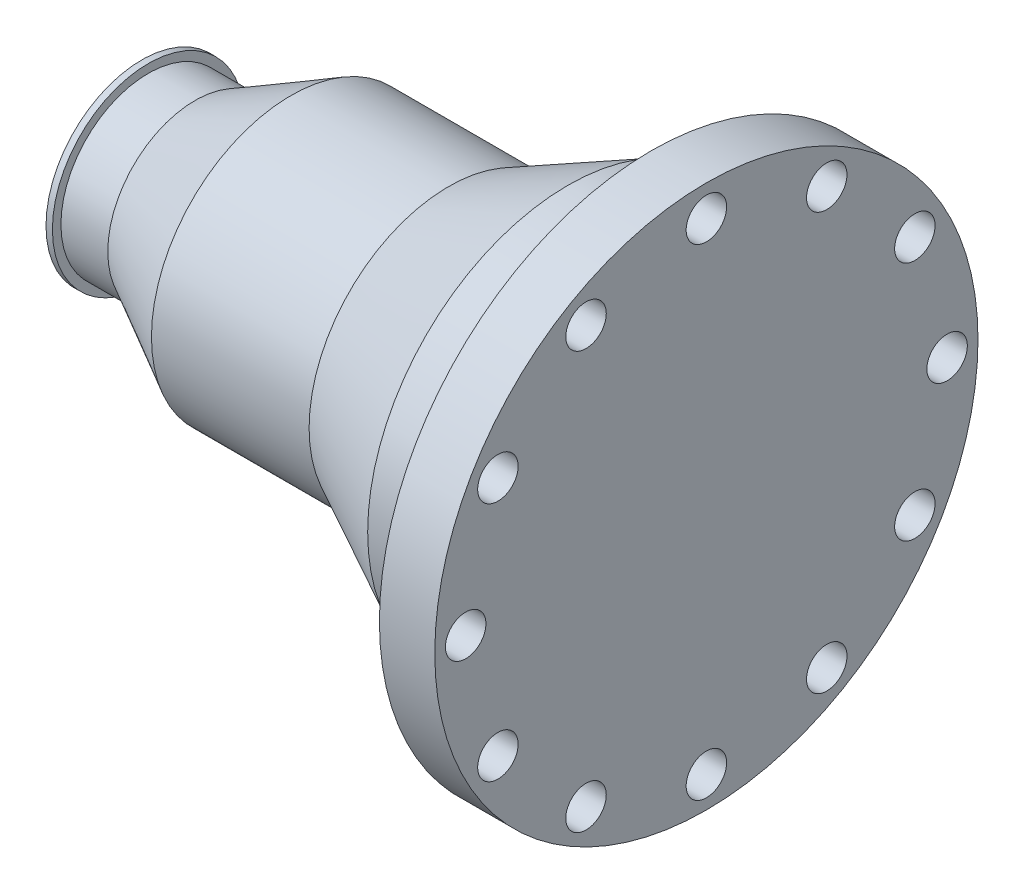
SolidWorks part; units mm, degrees
ref_plane "Спереди" through (0, 0, 0) normal (0, 0, 1) x (1, 0, 0)
ref_plane "Сверху" through (0, 0, 0) normal (0, 1, 0) x (1, 0, 0)
ref_plane "Справа" through (0, 0, 0) normal (1, 0, 0) x (0, 0, -1)
sketch "Эскиз1" plane through (0, 0, 0) normal (0, 0, 1) x (1, 0, 0)
  line L0 (0, 0) -> (265, 0)
  line L1 (0, 0) -> (0, 45)
  line L2 (0, 45) -> (3, 45)
  line L3 (3, 45) -> (3, 41)
  line L4 (3, 41) -> (25, 41)
  line L5 (25, 41) -> (70, 65.5)
  line L6 (70, 65.5) -> (144, 65.5)
  line L7 (144, 65.5) -> (200, 94)
  line L8 (200, 94) -> (220, 94)
  line L9 (220, 94) -> (220, 95)
  line L10 (220, 95) -> (239, 95)
  line L11 (239, 95) -> (239, 100)
  line L12 (239, 100) -> (239, 127.5)
  line L13 (239, 127.5) -> (265, 127.5)
  line L14 (265, 127.5) -> (265, 0)
revolve "Повернуть1" add sketch "Эскиз1" angle 360 about L0
sketch "Эскиз2" plane through (0, 0, 0) normal (0, 0, 1) x (1, 0, 0)
  line L0 (0, 0) -> (38, 0)
  line L1 (0, 0) -> (0, 31)
  line L2 (0, 45) -> (0, -45) construction
  line L3 (0, 31) -> (38, 31)
  line L4 (38, 31) -> (38, 0)
revolve "Вырез-Повернуть1" cut sketch "Эскиз2" angle 360 about L0
sketch "Эскиз3" plane through (0, 0, 0) normal (1, 0, 0) x (0, 0, -1)
  circle A0 centre (0, 113) radius 9.5
extrude "Вырез-Вытянуть1" cut sketch "Эскиз3" along normal through all
sketch "Эскиз4" plane through (0, 0, 0) normal (1, 0, 0) x (0, 0, -1)
  circle A0 centre (-56.5, 97.8609) radius 9.5
extrude "Вырез-Вытянуть2" cut sketch "Эскиз4" along normal through all
sketch "Эскиз5" plane through (0, 0, 0) normal (1, 0, 0) x (0, 0, -1)
  circle A0 centre (-97.8609, 56.5) radius 9.5
extrude "Вырез-Вытянуть3" cut sketch "Эскиз5" along normal through all
sketch "Эскиз6" plane through (0, 0, 0) normal (1, 0, 0) x (0, 0, -1)
  circle A0 centre (-113, 0) radius 9.5
extrude "Вырез-Вытянуть4" cut sketch "Эскиз6" along normal through all
sketch "Эскиз7" plane through (0, 0, 0) normal (1, 0, 0) x (0, 0, -1)
  circle A0 centre (-97.8609, -56.5) radius 9.5
extrude "Вырез-Вытянуть5" cut sketch "Эскиз7" along normal through all
sketch "Эскиз8" plane through (0, 0, 0) normal (1, 0, 0) x (0, 0, -1)
  circle A0 centre (-56.5, -97.8609) radius 9.5
extrude "Вырез-Вытянуть6" cut sketch "Эскиз8" along normal through all
sketch "Эскиз9" plane through (0, 0, 0) normal (1, 0, 0) x (0, 0, -1)
  circle A0 centre (0, -113) radius 9.5
extrude "Вырез-Вытянуть7" cut sketch "Эскиз9" along normal through all
sketch "Эскиз10" plane through (0, 0, 0) normal (1, 0, 0) x (0, 0, -1)
  circle A0 centre (56.5, -97.8609) radius 9.5
extrude "Вырез-Вытянуть8" cut sketch "Эскиз10" along normal through all
sketch "Эскиз11" plane through (0, 0, 0) normal (1, 0, 0) x (0, 0, -1)
  circle A0 centre (97.8609, -56.5) radius 9.5
extrude "Вырез-Вытянуть9" cut sketch "Эскиз11" along normal through all
sketch "Эскиз12" plane through (0, 0, 0) normal (1, 0, 0) x (0, 0, -1)
  circle A0 centre (113, 0) radius 9.5
extrude "Вырез-Вытянуть10" cut sketch "Эскиз12" along normal through all
sketch "Эскиз13" plane through (0, 0, 0) normal (1, 0, 0) x (0, 0, -1)
  circle A0 centre (97.8609, 56.5) radius 9.5
extrude "Вырез-Вытянуть11" cut sketch "Эскиз13" along normal through all
sketch "Эскиз14" plane through (0, 0, 0) normal (1, 0, 0) x (0, 0, -1)
  circle A0 centre (56.5, 97.8609) radius 9.5
extrude "Вырез-Вытянуть12" cut sketch "Эскиз14" along normal through all
